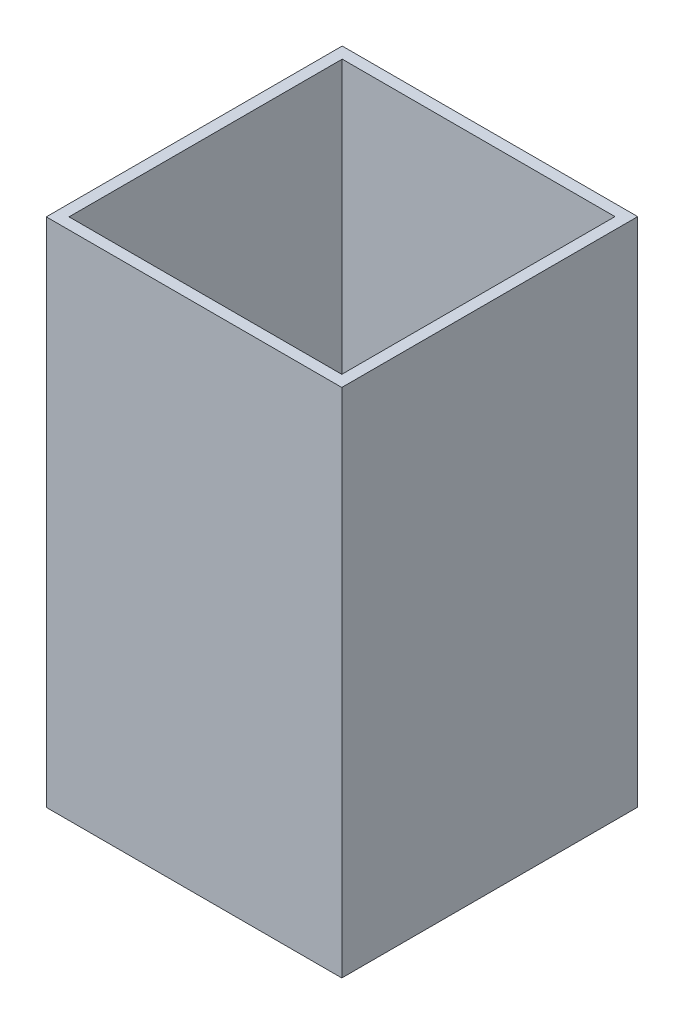
SolidWorks part; units mm, degrees
ref_plane "Plan de face" through (0, 0, 0) normal (0, 0, 1) x (1, 0, 0)
ref_plane "Plan de dessus" through (0, 0, 0) normal (0, 1, 0) x (1, 0, 0)
ref_plane "Plan de droite" through (0, 0, 0) normal (1, 0, 0) x (0, 0, -1)
sketch "Esquisse1" plane through (0, 0, 0) normal (0, 0, 1) x (1, 0, 0)
  line L1 (-130, 225) -> (130, 225)
  line L2 (-130, 225) -> (-130, -225)
  line L3 (-130, -225) -> (130, -225)
  line L4 (130, 225) -> (130, -225)
  point P4 (0, 225)
  point P6 (130, 0)
  dimension "D1" = 260
  dimension "D2" = 450
extrude "Boss.-Extru.1" add sketch "Esquisse1" along normal mid plane 260.36
sketch "Esquisse2" plane through (0, 225, 0) normal (0, 1, 0) x (1, 0, 0)
  line L0 (-130, -130.18) -> (-130, 130.18) construction
  line L1 (-120, 120.18) -> (120, 120.18)
  line L2 (-120, 120.18) -> (-120, -120.18)
  line L3 (-120, -120.18) -> (120, -120.18)
  line L4 (120, 120.18) -> (120, -120.18)
  line L5 (130, -130.18) -> (130, 130.18) construction
  line L6 (130, 130.18) -> (-130, 130.18) construction
  line L7 (130, -130.18) -> (-130, -130.18) construction
  dimension "D1" = 10
  dimension "D2" = 10
  dimension "D3" = 10
  dimension "D4" = 10
extrude "Enlèv. mat.-Extru.1" cut sketch "Esquisse2" against normal up to next
